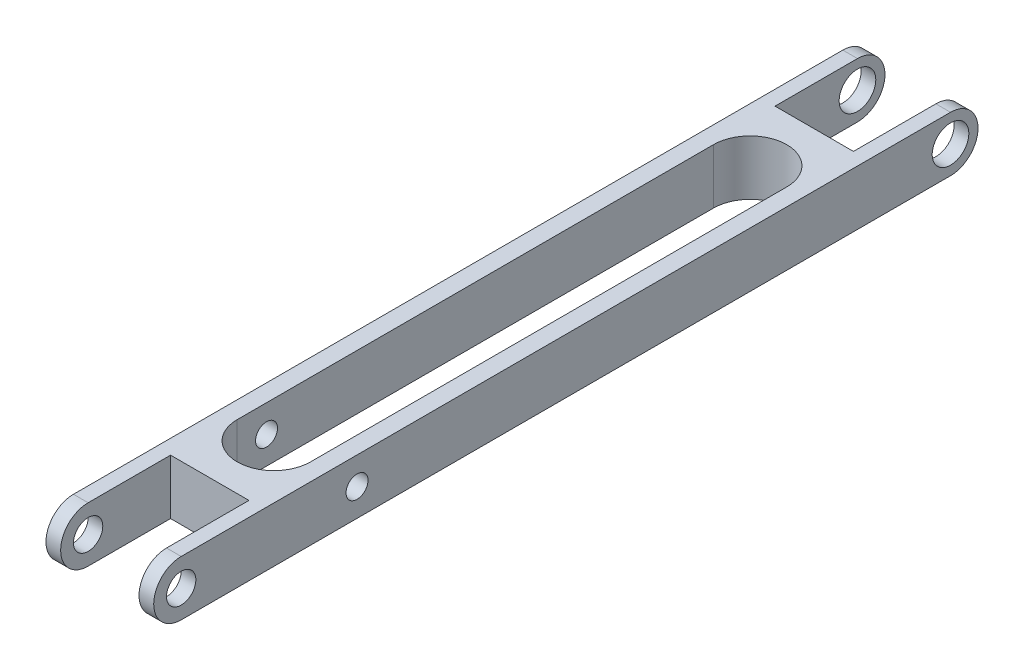
SolidWorks part; units mm, degrees
material "ABS"
ref_plane "前视基准面" through (0, 0, 0) normal (0, 0, 1) x (1, 0, 0)
ref_plane "上视基准面" through (0, 0, 0) normal (0, 1, 0) x (1, 0, 0)
ref_plane "右视基准面" through (0, 0, 0) normal (1, 0, 0) x (0, 0, -1)
sketch "草图2" plane through (0, 0, 0) normal (1, 0, 0) x (0, 0, -1)
  line L0 (-105, 7.5) -> (-105, -7.5) construction
  line L1 (-105, -7.5) -> (105, -7.5)
  line L3 (-105, 7.5) -> (105, 7.5)
  line L5 (-105, -7.5) -> (105, 7.5) construction
  line L6 (-105, 7.5) -> (105, -7.5) construction
  line L7 (105, 7.5) -> (105, -7.5) construction
  arc A0 (-105, 7.5) -> (-105, -7.5) centre (-105, 0) ccw
  arc A1 (105, 7.5) -> (105, -7.5) centre (105, 0) cw
  point P0 (0, 0)
  dimension "D1" = 15
  dimension "D2" = 210
extrude "凸台-拉伸1" add sketch "草图2" along normal blind 29.4
sketch "草图3" plane through (0, 7.5, 0) normal (0, 1, 0) x (1, 0, 0)
  line L1 (4, -112.5) -> (4, -82.5)
  line L2 (0, -112.5) -> (29.4, -112.5) construction
  line L3 (4, -82.5) -> (25.4, -82.5)
  line L4 (25.4, -82.5) -> (25.4, -112.5)
  line L5 (25.4, -112.5) -> (4, -112.5)
  line L6 (0, 105) -> (0, -105) construction
  line L7 (29.4, 105) -> (29.4, -105) construction
  line L10 (4, 112.5) -> (25.4, 112.5)
  line L14 (4, 112.5) -> (4, 82.5)
  line L15 (4, 82.5) -> (25.4, 82.5)
  line L16 (25.4, 82.5) -> (25.4, 112.5)
  line L17 (29.4, 105) -> (0, 105) construction
  dimension "D1" = 4
  dimension "D2" = 4
  dimension "D3" = 30
  dimension "D4" = 21.4
  dimension "D5" = 30
  dimension "D6" = 7.5
  dimension "D7" = 4
extrude "切除-拉伸1" cut sketch "草图3" against normal through all
sketch "草图4" plane through (29.4, 0, 0) normal (1, 0, 0) x (0, 0, -1)
  circle A0 centre (-105, 0) radius 4
  circle A1 centre (105, 0) radius 5
  dimension "D1" = 8
  dimension "D2" = 10
extrude "切除-拉伸2" cut sketch "草图4" against normal through all
sketch "草图5" plane through (0, -7.5, 0) normal (0, -1, 0) x (1, 0, 0)
  line L0 (14.7, 65) -> (14.7, -65) construction
  line L1 (24.7, 65) -> (24.7, -65)
  line L2 (4.7, 65) -> (4.7, -65)
  line L3 (0, 0) -> (14.7, 0) construction
  line L4 (0, 105) -> (0, -105) construction
  arc A0 (24.7, 65) -> (4.7, 65) centre (14.7, 65) ccw
  arc A1 (4.7, -65) -> (24.7, -65) centre (14.7, -65) ccw
  point P2 (14.7, 0)
  dimension "D1" = 20
  dimension "D2" = 14.7
  dimension "D3" = 130
extrude "切除-拉伸3" cut sketch "草图5" against normal through all
sketch "草图6" plane through (0, 0, 0) normal (-1, 0, 0) x (0, 0, 1)
  line L0 (57, 0) -> (0, 0) construction
  circle A1 centre (57, 0) radius 3
  circle A3 centre (105, 0) radius 4 construction
  dimension "D1" = 48
  dimension "D2" = 6
extrude "切除-拉伸4" cut sketch "草图6" against normal through all
